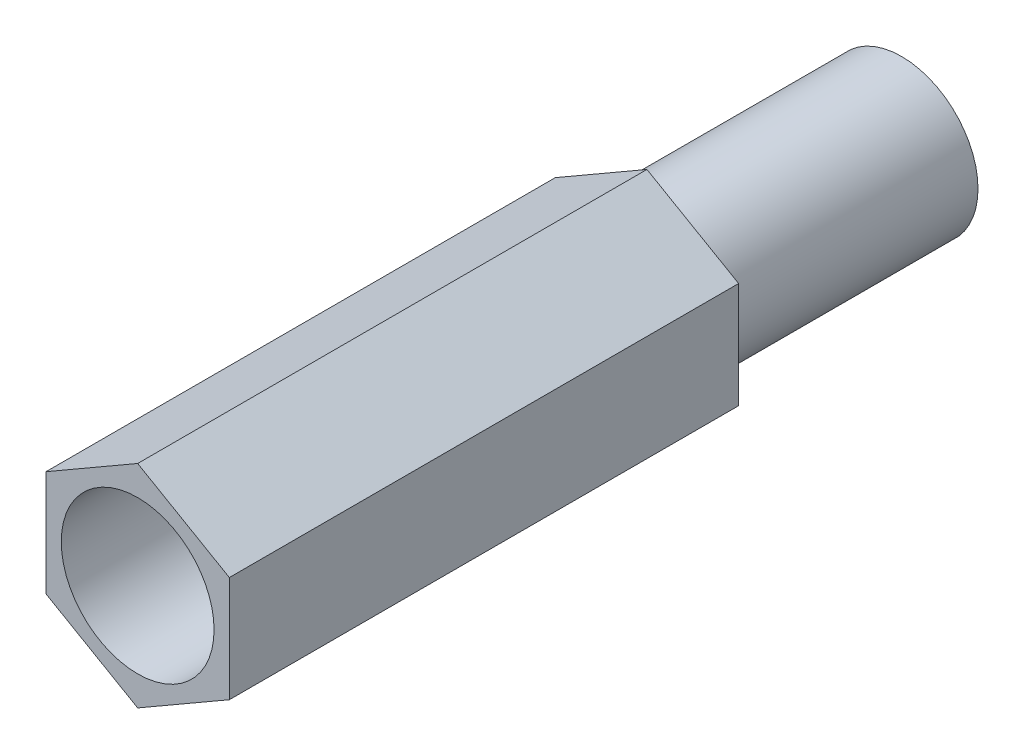
SolidWorks part; units mm, degrees
ref_plane "前视基准面" through (0, 0, 0) normal (0, 0, 1) x (1, 0, 0)
ref_plane "上视基准面" through (0, 0, 0) normal (0, 1, 0) x (1, 0, 0)
ref_plane "右视基准面" through (0, 0, 0) normal (1, 0, 0) x (0, 0, -1)
sketch "草图1" plane through (0, 0, 0) normal (0, 0, 1) x (1, 0, 0)
  line L1 (0, 2.0785) -> (-1.8, 1.0392)
  line L2 (-1.8, 1.0392) -> (-1.8, -1.0392)
  line L3 (-1.8, -1.0392) -> (0, -2.0785)
  line L4 (0, -2.0785) -> (1.8, -1.0392)
  line L5 (1.8, -1.0392) -> (1.8, 1.0392)
  line L6 (1.8, 1.0392) -> (0, 2.0785)
  circle A0 centre (0, 0) radius 1.8 construction
  circle A1 centre (0, 0) radius 1.5
extrude "凸台-拉伸1" add sketch "草图1" along normal blind 10
sketch "草图2" plane through (0, 0, 0) normal (0, 0, -1) x (-1, 0, 0)
  circle A0 centre (0, 0) radius 1.5
extrude "凸台-拉伸2" add sketch "草图2" along normal mid plane 10 contours A0
